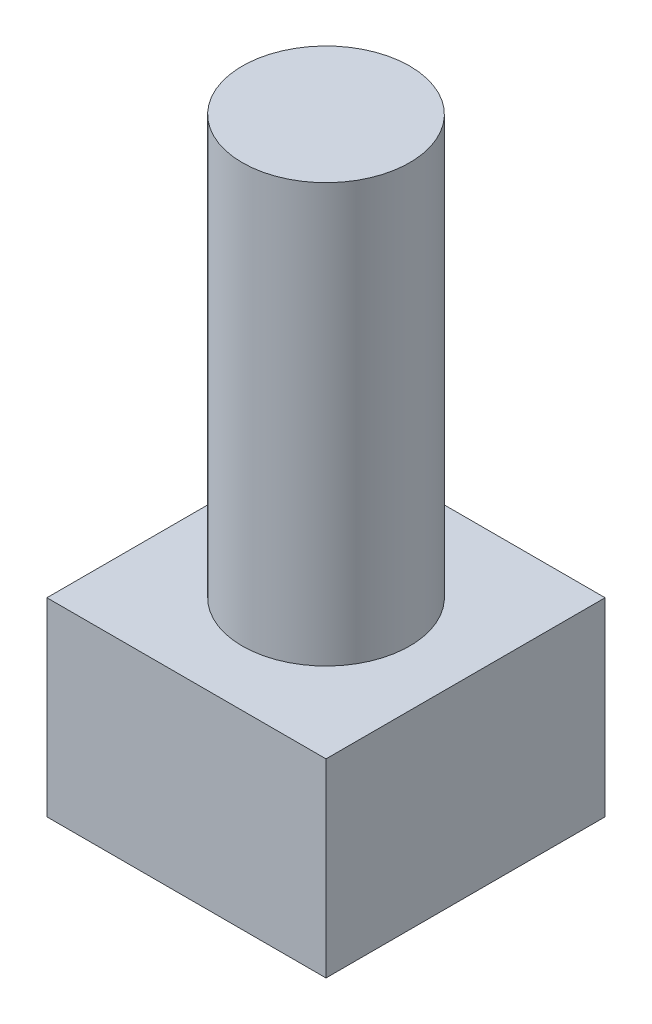
SolidWorks part; units mm, degrees
ref_plane "Front Plane" through (0, 0, 0) normal (0, 0, 1) x (1, 0, 0)
ref_plane "Top Plane" through (0, 0, 0) normal (0, 1, 0) x (1, 0, 0)
ref_plane "Right Plane" through (0, 0, 0) normal (1, 0, 0) x (0, 0, -1)
sketch "Sketch1" plane through (0, 0, 0) normal (0, 1, 0) x (1, 0, 0)
  line L1 (-5, 5) -> (5, 5)
  line L2 (-5, 5) -> (-5, -5)
  line L3 (-5, -5) -> (5, -5)
  line L4 (5, 5) -> (5, -5)
  line L5 (-5, 5) -> (5, -5) construction
  line L6 (-5, -5) -> (5, 5) construction
  point P0 (0, 0)
  dimension "D1" = 10
  dimension "D2" = 10
extrude "Boss-Extrude1" add sketch "Sketch1" along normal blind 6.8
sketch "Sketch2" plane through (0, 6.8, 0) normal (0, 1, 0) x (1, 0, 0)
  circle A0 centre (0, 0) radius 3
  dimension "D1" = 6
extrude "Boss-Extrude2" add sketch "Sketch2" along normal blind 15
